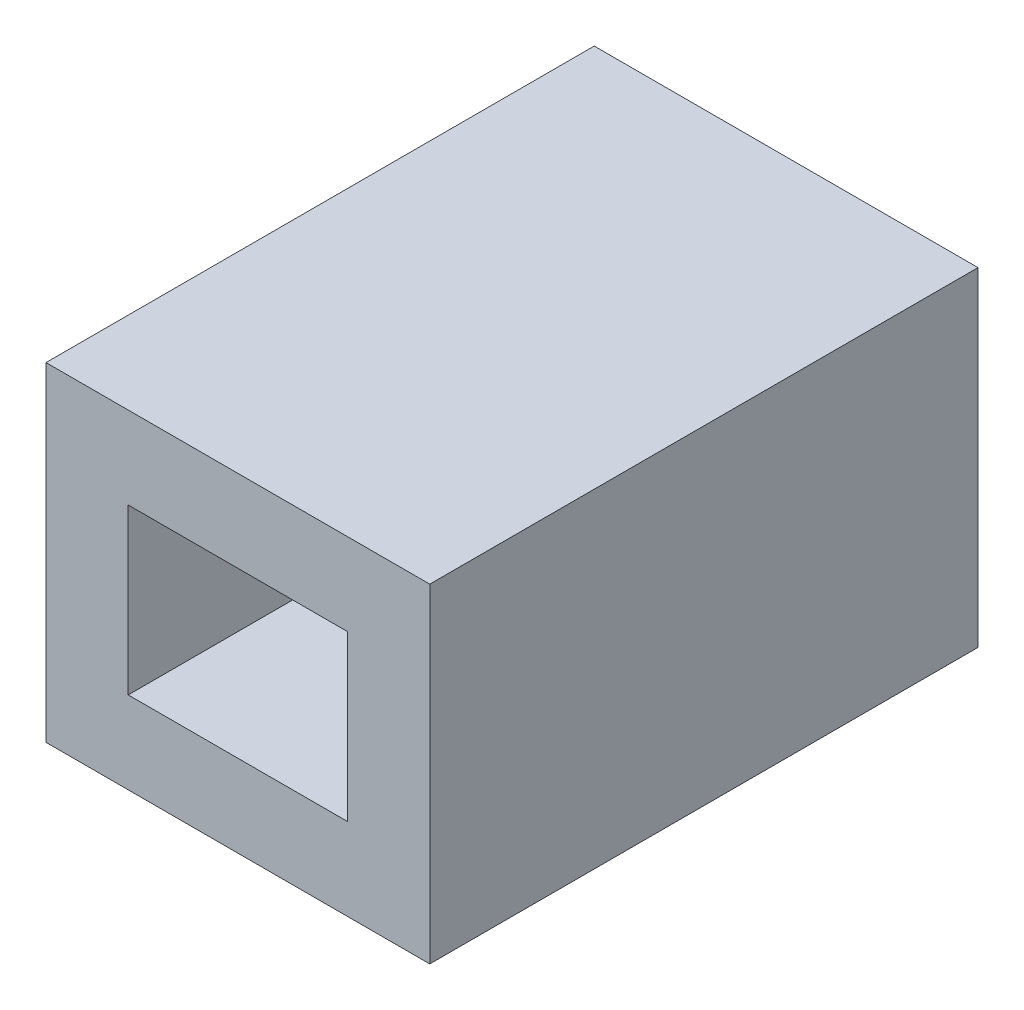
SolidWorks part; units mm, degrees
ref_plane "Plan de face" through (0, 0, 0) normal (0, 0, 1) x (1, 0, 0)
ref_plane "Plan de dessus" through (0, 0, 0) normal (0, 1, 0) x (1, 0, 0)
ref_plane "Plan de droite" through (0, 0, 0) normal (1, 0, 0) x (0, 0, -1)
sketch "Esquisse1" plane through (0, 0, 0) normal (0, 0, 1) x (1, 0, 0)
  line L1 (0, 12) -> (14, 12)
  line L2 (0, 12) -> (0, 0)
  line L3 (0, 0) -> (14, 0)
  line L4 (14, 12) -> (14, 0)
  line L5 (3, 9) -> (11, 9)
  line L6 (3, 9) -> (3, 3)
  line L7 (3, 3) -> (11, 3)
  line L8 (11, 9) -> (11, 3)
  dimension "D1" = 14
  dimension "D2" = 12
  dimension "D3" = 3
  dimension "D4" = 3
  dimension "D5" = 8
  dimension "D6" = 6
extrude "Boss.-Extru.1" add sketch "Esquisse1" along normal blind 20
